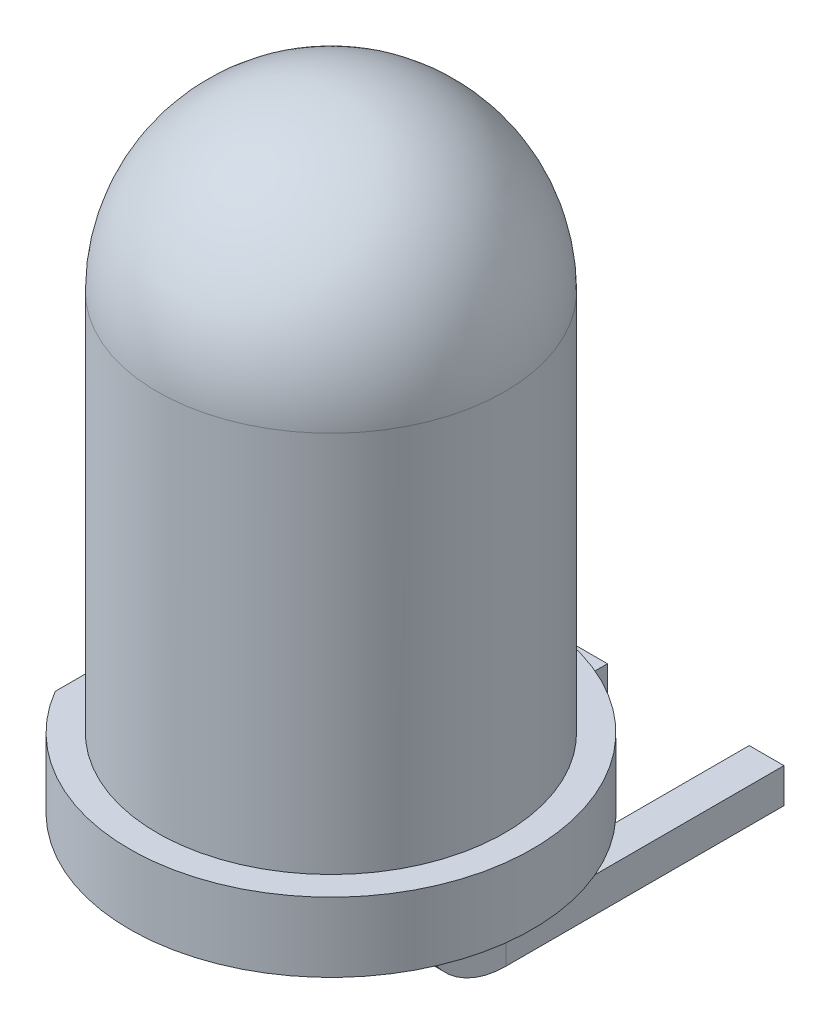
SolidWorks part; units mm, degrees
ref_plane "Front Plane" through (0, 0, 0) normal (0, 0, 1) x (1, 0, 0)
ref_plane "Top Plane" through (0, 0, 0) normal (0, 1, 0) x (1, 0, 0)
ref_plane "Right Plane" through (0, 0, 0) normal (1, 0, 0) x (0, 0, -1)
sketch "Sketch1" plane through (0, 0, 0) normal (0, 0, -1) x (1, 0, 0)
  line L0 (0, 0) -> (0, -9)
  line L1 (2.5, -6.5) -> (2.5, -1)
  line L2 (2.9, 0) -> (0, 0)
  line L3 (2.5, -1) -> (2.9, -1)
  line L4 (2.9, -1) -> (2.9, 0)
  arc A0 (2.5, -6.5) -> (0, -9) centre (0, -6.5) cw
  point P3 (0, -6.5348)
  dimension "D1" = 2.5
  dimension "D2" = 2.9
  dimension "D3" = 1
  dimension "D4" = 9
revolve "Revolve1" add sketch "Sketch1" angle 360 about L0
sketch "Sketch2" plane through (0, 0, 0) normal (0, -1, 0) x (-1, 0, 0)
  line L1 (2.9, 1.4697) -> (2.5, 1.4697)
  line L2 (2.9, 1.4697) -> (2.9, -1.4697)
  line L3 (2.9, -1.4697) -> (2.5, -1.4697)
  line L4 (2.5, 1.4697) -> (2.5, -1.4697)
  circle A0 centre (0, 0) radius 2.5 construction
  circle A1 centre (0, 0) radius 2.9 construction
extrude "Cut-Extrude1" cut sketch "Sketch2" against normal through all
sketch "Sketch3" plane through (0, 0, 0) normal (0, -1, 0) x (-1, 0, 0)
  line L0 (0, 1.7562) -> (0, 0) construction
  line L1 (0, 0) -> (1.27, 0) construction
  line L2 (-1.02, 0.25) -> (-1.02, -0.25)
  line L3 (1.02, 0.25) -> (1.52, 0.25)
  line L4 (1.02, 0.25) -> (1.02, -0.25)
  line L5 (1.02, -0.25) -> (1.52, -0.25)
  line L6 (1.52, 0.25) -> (1.52, -0.25)
  line L7 (1.02, 0.25) -> (1.52, -0.25) construction
  line L8 (1.02, -0.25) -> (1.52, 0.25) construction
  line L9 (-1.02, -0.25) -> (-1.52, -0.25)
  line L10 (-1.52, 0.25) -> (-1.52, -0.25)
  line L11 (-1.02, 0.25) -> (-1.52, 0.25)
  dimension "D1" = 0.5
  dimension "D2" = 1.27
ref_plane "Plane1" through (-1.27, 0, 0) normal (1, 0, 0) x (0, 0, -1)
sketch "Sketch4" plane through (-1.27, 0, 0) normal (1, 0, 0) x (0, 0, -1)
  line L0 (0, 0) -> (0, -0.4)
  line L1 (1, -1.4) -> (5, -1.4)
  arc A0 (0, -0.4) -> (1, -1.4) centre (1, -0.4) ccw
  dimension "D3" = 5
  dimension "D2" = 1
  dimension "D1" = 0.4
sweep "Sweep1" add profiles "Sketch3" path "Sketch4"
